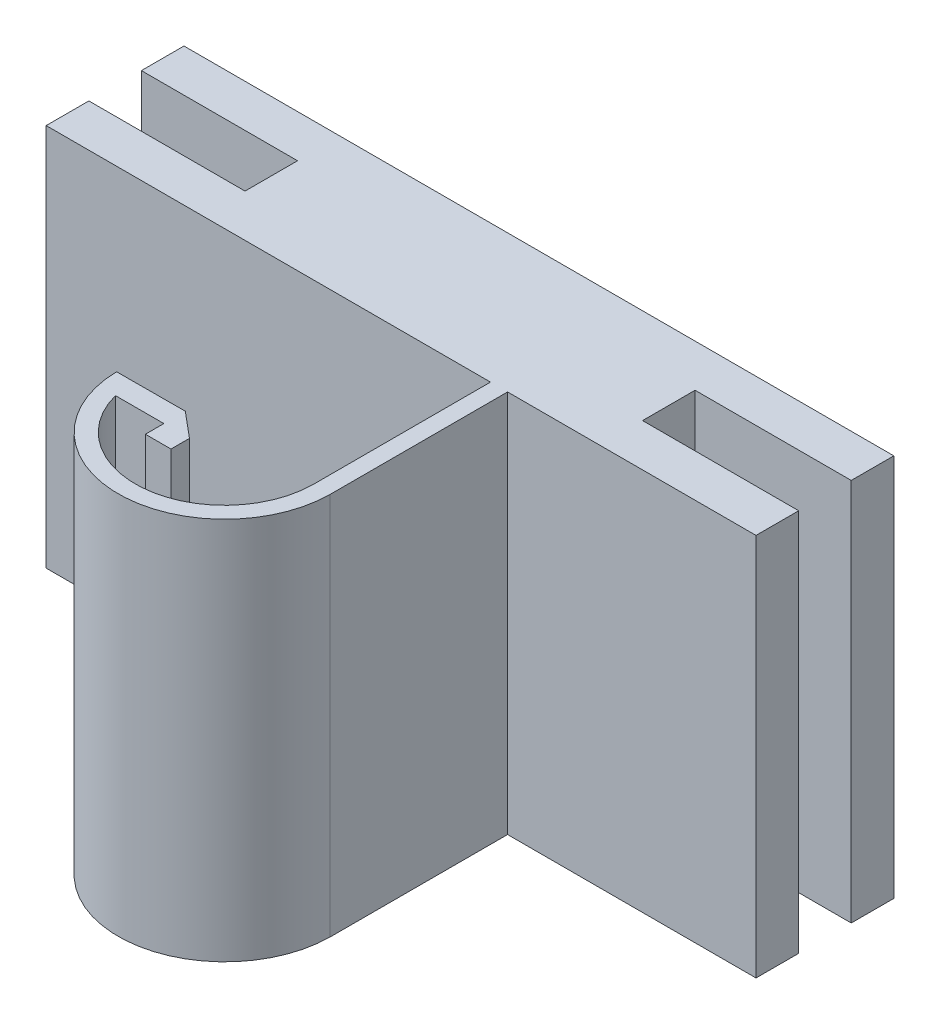
SolidWorks part; units mm, degrees
ref_plane "Front Plane" through (0, 0, 0) normal (0, 0, 1) x (1, 0, 0)
ref_plane "Top Plane" through (0, 0, 0) normal (0, 1, 0) x (1, 0, 0)
ref_plane "Right Plane" through (0, 0, 0) normal (1, 0, 0) x (0, 0, -1)
sketch "Sketch2" plane through (0, 0, 0) normal (0, 1, 0) x (1, 0, 0)
  line L0 (-28.3495, 21.9641) -> (-17.3495, 21.9641)
  line L1 (-28.3495, 28.6641) -> (21.6505, 28.6641)
  line L2 (-28.3495, 28.6641) -> (-28.3495, 25.6641)
  line L3 (-28.3495, 25.6641) -> (-17.3495, 25.6641)
  line L4 (21.6505, 28.6641) -> (21.6505, 25.6641)
  line L5 (-28.3495, 21.9641) -> (-28.3495, 18.957)
  line L6 (-28.3495, 18.957) -> (2.9478, 18.957)
  line L7 (21.6505, 21.9641) -> (21.6505, 18.957)
  line L8 (-17.3495, 25.6641) -> (-17.3495, 21.9641)
  line L9 (10.6505, 25.6641) -> (10.6505, 21.9641)
  line L10 (10.6505, 21.9641) -> (21.6505, 21.9641)
  line L11 (10.6505, 25.6641) -> (21.6505, 25.6641)
  line L12 (-10.8477, 6.4173) -> (-6.0262, 6.4324)
  line L13 (-6.0262, 6.4324) -> (-4.2225, 4.9232)
  line L14 (4.1505, 18.957) -> (4.1505, 6.457)
  line L15 (-4.2225, 4.9232) -> (-4.2225, 3.6222)
  line L16 (-4.2225, 3.6222) -> (-6.0262, 3.6222)
  line L17 (2.9478, 6.4407) -> (2.9478, 18.957)
  line L18 (4.1505, 18.957) -> (21.6505, 18.957)
  line L19 (-6.0262, 3.6222) -> (-6.0262, 4.9232)
  line L20 (-6.0262, 4.9232) -> (-9.4379, 4.9232)
  arc A0 (-10.8477, 6.4173) -> (4.1505, 6.457) centre (-3.3488, 6.5292) ccw
  arc A1 (-9.4379, 4.9232) -> (2.9478, 6.4407) centre (-3.3488, 6.5292) ccw
  dimension "D1" = 50
  dimension "D2" = 3
  dimension "D3" = 3.7
  dimension "D4" = 28
  dimension "D5" = 11
extrude "Boss-Extrude2" add sketch "Sketch2" along normal blind 27
